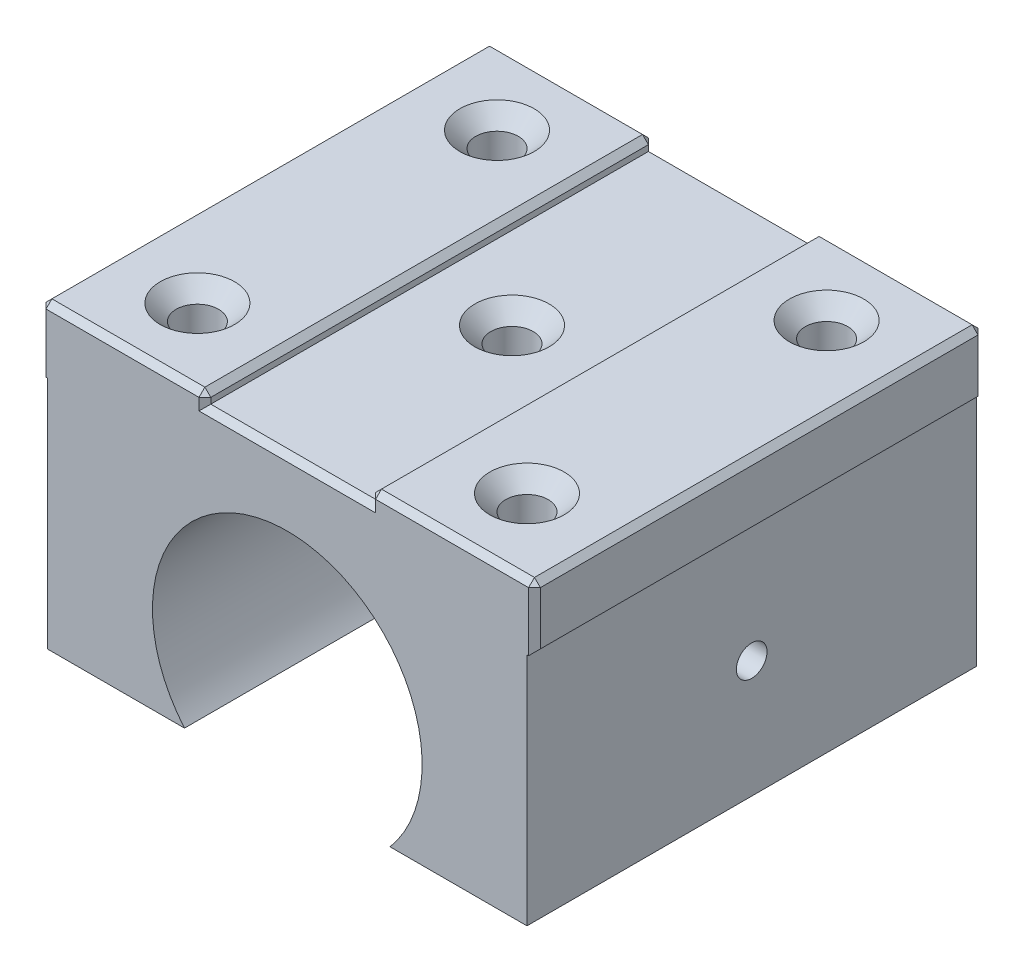
SolidWorks part; units mm, degrees
ref_plane "Front Plane" through (0, 0, 0) normal (0, 0, 1) x (1, 0, 0)
ref_plane "Top Plane" through (0, 0, 0) normal (0, 1, 0) x (1, 0, 0)
ref_plane "Right Plane" through (0, 0, 0) normal (1, 0, 0) x (0, 0, -1)
sketch "Sketch1" plane through (0, 0, 0) normal (0, 0, 1) x (1, 0, 0)
  line L0 (0, 0) -> (0, 11.43) construction
  line L1 (-20.32, -7.3995) -> (-8.7116, -7.3995)
  line L2 (-20.32, -7.3995) -> (-20.32, 12.5005)
  line L3 (-20.955, 18.0005) -> (20.955, 18.0005)
  line L4 (20.32, -7.3995) -> (20.32, 12.5005)
  line L5 (8.7116, -7.3995) -> (20.32, -7.3995)
  line L6 (20.32, 12.5005) -> (20.955, 12.5005)
  line L7 (-20.955, 18.0005) -> (20.955, 18.0005)
  line L8 (-20.955, 18.0005) -> (-20.955, 12.5005)
  line L9 (-20.955, 12.5005) -> (-20.32, 12.5005)
  line L10 (20.955, 18.0005) -> (20.955, 12.5005)
  line L11 (0, 18.0005) -> (0, 51.8376) construction
  line L13 (-20.955, 18.0005) -> (20.955, 18.0005)
  arc A0 (8.7116, -7.3995) -> (-8.7116, -7.3995) centre (0, 0) ccw
  dimension "D1" = 22.86
  dimension "D2" = 25.4
  dimension "D3" = 40.64
  dimension "D4" = 18.0005
  dimension "D5" = 5.5
  dimension "D6" = 41.91
extrude "Boss-Extrude1" add sketch "Sketch1" along normal blind 38.1 contours A0 L0 L3 L8 L9 L2 L1 | L0 A0 L5 L4 L6 L10 L7
sketch "Sketch3" plane through (0, 18.0005, 0) normal (0, 1, 0) x (1, 0, 0)
  line L0 (0, 0) -> (0, -38.1) construction
  line L1 (-20.955, 0) -> (20.955, 0) construction
  line L2 (-20.955, -38.1) -> (20.955, -38.1) construction
  line L3 (-20.955, -19.05) -> (20.955, -19.05) construction
  line L4 (-20.955, -38.1) -> (-20.955, 0) construction
  line L5 (20.955, -38.1) -> (20.955, 0) construction
  line L6 (-13.97, -6.35) -> (-13.97, -31.75) construction
  line L7 (-6.985, 0) -> (-6.985, -38.1) construction
  line L8 (6.985, 0) -> (6.985, -38.1) construction
  line L11 (20.955, 0) -> (-20.955, 0)
  line L12 (-20.955, 0) -> (-20.955, -38.1)
  line L13 (-20.955, -38.1) -> (20.955, -38.1)
  line L14 (20.955, -38.1) -> (20.955, 0)
  line L15 (20.955, 0) -> (-20.955, 0) construction
  line L16 (-20.955, 0) -> (-20.955, -38.1) construction
  line L17 (-20.955, -38.1) -> (20.955, -38.1) construction
  line L18 (20.955, -38.1) -> (20.955, 0) construction
  circle A0 centre (-13.97, -6.35) radius 1
  circle A1 centre (13.97, -6.35) radius 1
  circle A2 centre (-13.97, -31.75) radius 1
  circle A3 centre (13.97, -31.75) radius 1
  circle A4 centre (0, -19.05) radius 1
  dimension "D3" = 2
  dimension "D4" = 2
  dimension "D1" = 27.94
  dimension "D2" = 25.4
  dimension "D5" = 0
sketch "Sketch4" plane through (0, 0, 38.1) normal (0, 0, 1) x (1, 0, 0)
  line L0 (-6.985, 18.0005) -> (-6.985, 17.0005)
  line L1 (-6.985, 17.0005) -> (6.985, 17.0005)
  line L2 (6.985, 17.0005) -> (6.985, 18.0005)
  dimension "D1" = 1
sketch "Sketch9" plane through (0, 18.0005, 0) normal (0, 1, 0) x (1, 0, 0)
  point P0 (-13.97, -6.35)
  point P3 (-13.97, -31.75)
  point P6 (13.97, -31.75)
  point P9 (13.97, -6.35)
hole_wizard "CSK for M3 Countersunk Flat Head Screw2" positions "Sketch9" profile "Sketch8" countersink size "M3" standard "ISO"
sketch "Sketch8" plane through (-13.97, 18.0005, 6.35) normal (1, 0, 0) x (0, 0, 1)
  line L0 (0, 0) -> (0, 11.0815)
  line L1 (0, 11.0815) -> (1.8, 10)
  line L2 (1.8, 10) -> (1.8, 1.35)
  line L3 (1.8, 1.35) -> (3.15, 0)
  line L5 (3.15, 0) -> (0, 0)
  line L6 (-1.8, 1.35) -> (-3.15, 0) construction
  line L10 (0, 11.0815) -> (-1.8, 10) construction
  line L11 (0, -6.35) -> (0, 107.95) construction
  dimension "Hole Dia." = 3.6
  dimension "Hole Depth" = 10
  dimension "Near C'Sink Dia." = 6.3
  dimension "Near C'Sink Angle" = 90
  dimension "Drill Angle" = 118
extrude "Cut-Extrude1" cut sketch "Sketch4" against normal through all and the other way through all
sketch "Sketch11" plane through (0, 17.0005, 0) normal (0, 1, 0) x (1, 0, 0)
  circle A0 centre (0, -19.05) radius 1 construction
  circle A1 centre (0, -19.05) radius 1
  point P2 (0, -19.05)
hole_wizard "CSK for M3 Countersunk Flat Head Screw3" positions "Sketch11" profile "Sketch12" countersink size "M3" standard "ISO"
sketch "Sketch12" plane through (0, 17.0005, 19.05) normal (1, 0, 0) x (0, 0, 1)
  line L0 (0, 0) -> (0, 11.0815)
  line L1 (0, 11.0815) -> (1.8, 10)
  line L2 (1.8, 10) -> (1.8, 1.35)
  line L3 (1.8, 1.35) -> (3.15, 0)
  line L5 (3.15, 0) -> (0, 0)
  line L6 (-1.8, 1.35) -> (-3.15, 0) construction
  line L10 (0, 11.0815) -> (-1.8, 10) construction
  line L11 (0, -6.35) -> (0, 107.95) construction
  dimension "Hole Dia." = 3.6
  dimension "Hole Depth" = 10
  dimension "Near C'Sink Dia." = 6.3
  dimension "Near C'Sink Angle" = 90
  dimension "Drill Angle" = 118
chamfer "Chamfer1" distance 0.5 angle 45 20 edges at (20.955, 12.5005, 19.05) (13.97, 18.0005, 0) (13.97, 18.0005, 38.1) (20.955, 15.2505, 0) (20.955, 15.2505, 38.1) (6.985, 17.5005, 38.1) (6.985, 17.5005, 0) (20.955, 18.0005, 19.05) (6.985, 18.0005, 19.05) (-6.985, 17.5005, 38.1) (-6.985, 17.5005, 0) (-13.97, 18.0005, 0) (-13.97, 18.0005, 38.1) (-6.985, 18.0005, 19.05) (-20.955, 18.0005, 19.05) (-20.955, 12.5005, 19.05) (0, 17.0005, 38.1) (0, 17.0005, 0) (-20.955, 15.2505, 0) (-20.955, 15.2505, 38.1)
sketch "Sketch13" plane through (-20.32, 0, 0) normal (-1, 0, 0) x (0, 0, 1)
  line L0 (0, 12.5005) -> (38.1, -7.3995) construction
  line L1 (0, -7.3995) -> (38.1, 12.5005) construction
  point P10 (19.05, 2.5505)
hole_wizard "CSK for M2 Countersunk Flat Head Screw2" positions "Sketch13" profile "Sketch14" countersink size "M2" standard "ISO" end condition through all
sketch "Sketch14" plane through (-20.32, 2.5505, 19.05) normal (0, 1, 0) x (0, 0, 1)
  line L0 (0, 0) -> (0, 41.275)
  line L1 (0, 41.275) -> (1.3, 41.275)
  line L2 (1.3, 41.275) -> (1.3, 0.9)
  line L3 (1.3, 0.9) -> (2.2, 0)
  line L5 (2.2, 0) -> (0, 0)
  line L6 (-1.3, 0.9) -> (-2.2, 0) construction
  line L11 (0, -6.35) -> (0, 107.95) construction
  dimension "Thru Hole Dia." = 2.6
  dimension "Thru Hole Depth" = 41.275
  dimension "Near C'Sink Dia." = 4.4
  dimension "Near C'Sink Angle" = 90
ref_plane "Plane1" through (0, 0, 33.1) normal (0, 0, 1) x (1, 0, 0)
ref_plane "Plane2" through (0, 0, 19.05) normal (0, 0, 1) x (1, 0, 0)
ref_plane "Plane3" through (0, 0, 5) normal (0, 0, -1) x (-1, 0, 0)
sketch "Sketch16" plane through (0, 0, 33.1) normal (0, 0, 1) x (1, 0, 0)
  line L0 (-8.0822, 8.0822) -> (0, 0) construction
  line L1 (0, 0) -> (8.0822, 8.0822) construction
  line L2 (0, 0) -> (0, 11.43) construction
  line L3 (-7.3751, 7.3751) -> (-8.7893, 8.7893)
  arc A0 (8.7116, -7.3995) -> (-8.7116, -7.3995) centre (0, 0) ccw construction
  arc A1 (-7.3751, 7.3751) -> (-8.7893, 8.7893) centre (-8.0822, 8.0822) ccw
  dimension "D2" = 2
  dimension "D1" = 90
revolve "Revolve4" add sketch "Sketch16" angle 360 about L0
mirror "Mirror1" about plane through (0, 0, 0) normal (1, 0, 0) of "Revolve4"
pattern_linear "LPattern1" count 10 spacing 3.1222 along (0, 0, -1) of "Mirror1", "Revolve4"
